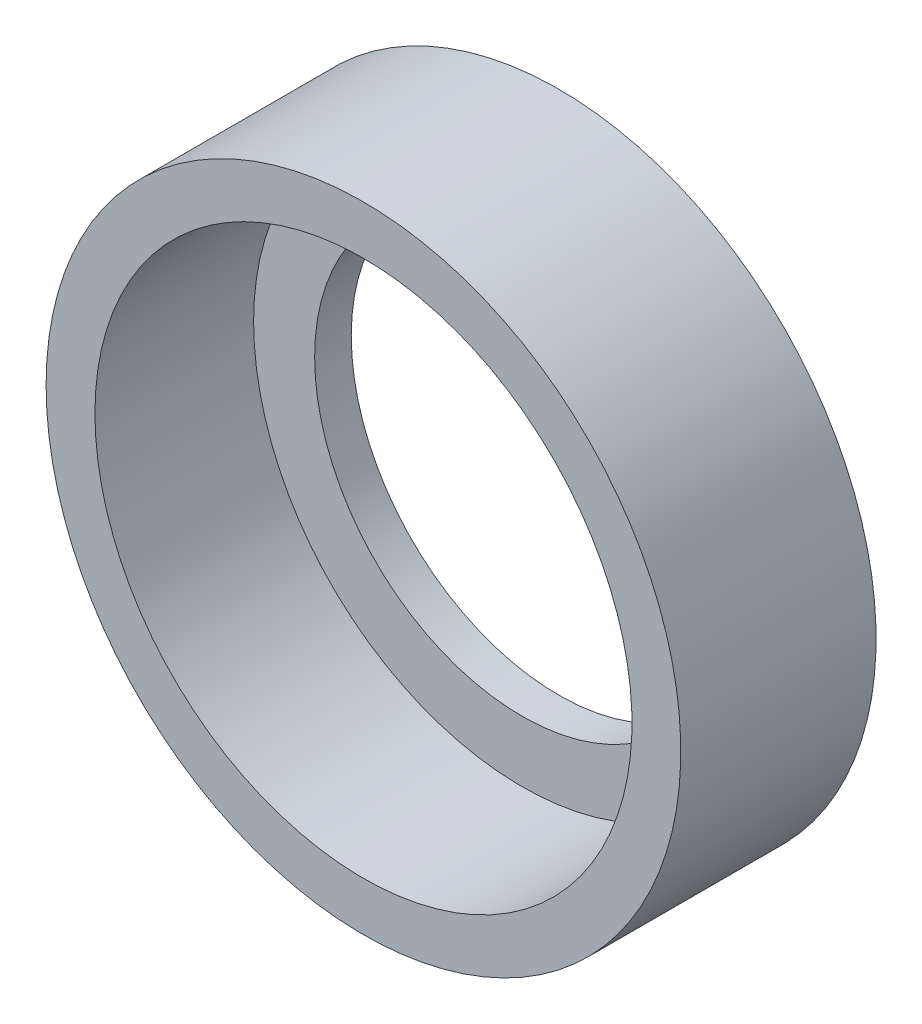
SolidWorks part; units mm, degrees
material "Caoutchouc"
ref_plane "Plan de face" through (0, 0, 0) normal (0, 0, 1) x (1, 0, 0)
ref_plane "Plan de dessus" through (0, 0, 0) normal (0, 1, 0) x (1, 0, 0)
ref_plane "Plan de droite" through (0, 0, 0) normal (1, 0, 0) x (0, 0, -1)
sketch "Esquisse1" plane through (0, 0, 0) normal (1, 0, 0) x (0, 0, -1)
  line L0 (0, 0) -> (-6.4375, 0) construction
  line L1 (-8, 13) -> (-8, 11)
  line L2 (-8, 11) -> (-1.5, 11)
  line L3 (-1.5, 11) -> (-1.5, 8.5)
  line L4 (-1.5, 8.5) -> (0, 8.5)
  line L5 (0, 8.5) -> (0, 13)
  line L6 (0, 13) -> (-8, 13)
  dimension "D1" = 26
  dimension "D2" = 22
  dimension "D3" = 8
  dimension "D4" = 1.5
  dimension "D5" = 17
revolve "Révolution1" add sketch "Esquisse1" angle 360 about L0
